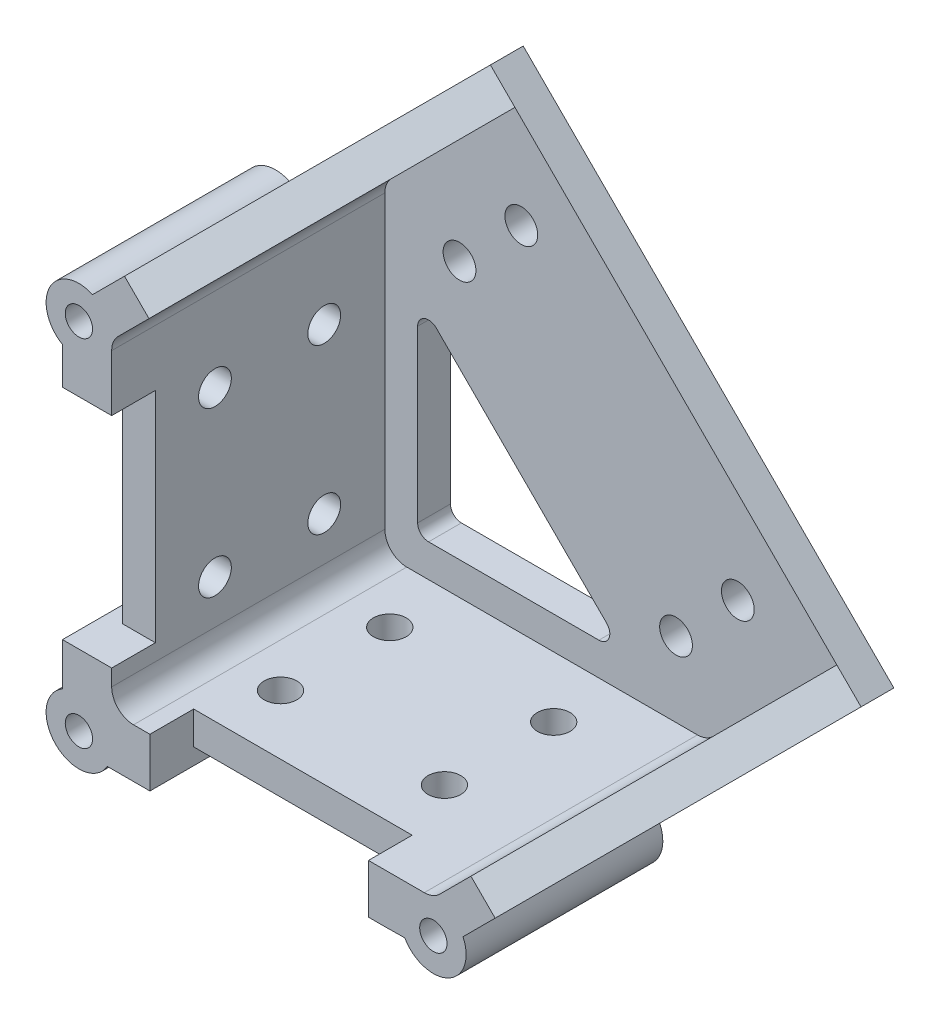
SolidWorks part; units mm, degrees
material "6061 合金"
ref_plane "前视基准面" through (0, 0, 0) normal (0, 0, 1) x (1, 0, 0)
ref_plane "上视基准面" through (0, 0, 0) normal (0, 1, 0) x (1, 0, 0)
ref_plane "右视基准面" through (0, 0, 0) normal (1, 0, 0) x (0, 0, -1)
sketch "草图1" plane through (0, 0, 0) normal (0, 0, 1) x (1, 0, 0)
  line L0 (-12.5966, 12.5) -> (15.5, 12.5) construction
  line L1 (-15.5, -15.5) -> (15.5, -15.5) construction
  line L2 (-15.5, -15.5) -> (-15.5, 15.5) construction
  line L3 (-15.5, 15.5) -> (15.5, 15.5) construction
  line L4 (15.5, -15.5) -> (15.5, 15.5) construction
  line L5 (-15.5, -15.5) -> (15.5, 15.5) construction
  line L6 (-15.5, 15.5) -> (15.5, -15.5) construction
  line L7 (12.5, 15.5) -> (12.5, -18.9326) construction
  line L8 (-7.5, -17) -> (-7.5, -15.5)
  line L9 (-7.5, 15.5) -> (-7.5, -18.9326) construction
  line L10 (-7.5, -15.5) -> (12.5, -15.5)
  line L11 (-15.5, 12.5) -> (-15.5, -7.5)
  line L12 (-12.9019, -17) -> (-7.5, -17)
  line L13 (-15.5, -7.5) -> (-17, -7.5)
  line L14 (15.5, 12.5) -> (15.5, 3)
  line L15 (15.5, -3) -> (15.5, -15.5)
  line L16 (3, 15.5) -> (12.5, 15.5)
  line L17 (-15.5, 15.5) -> (-3, 15.5)
  line L18 (-18.5, 12.5) -> (-15.5, 12.5)
  line L19 (-17, -7.5) -> (-17, -12.9019)
  line L20 (12.5, 12.5) -> (12.5, -12.5)
  line L21 (12.5, -15.5) -> (12.5, -18.5)
  line L22 (12.5, 15.5) -> (15.5, 15.5)
  line L23 (15.5, 15.5) -> (15.5, 12.5)
  line L24 (12.5, -12.5) -> (-12.5, -12.5)
  line L25 (-12.5, -12.5) -> (-12.5, 12.5)
  line L26 (-12.5, 12.5) -> (12.5, 12.5)
  circle A0 centre (0, 15.5) radius 1.5
  circle A1 centre (15.5, 0) radius 1.5
  circle A2 centre (-15.5, -15.5) radius 1.25
  arc A3 (3, 15.5) -> (-3, 15.5) centre (0, 15.5) ccw
  arc A4 (15.5, -3) -> (15.5, 3) centre (15.5, 0) ccw
  arc A5 (-17, -12.9019) -> (-12.9019, -17) centre (-15.5, -15.5) ccw
  arc A6 (-15.5, 15.5) -> (-18.5, 12.5) centre (-15.5, 12.5) ccw
  arc A7 (12.5, -18.5) -> (15.5, -15.5) centre (12.5, -15.5) ccw
  circle A9 centre (0, 15.5) radius 3 construction
  circle A10 centre (15.5, 0) radius 3 construction
  point P0 (0, 0)
  dimension "D6" = 3
  dimension "D7" = 3
  dimension "D8" = 2.5
  dimension "D10" = 6
  dimension "D12" = 1.5
  dimension "D1" = 31
  dimension "D2" = 3
  dimension "D3" = 3
  dimension "D11" = 1.5
  dimension "D4" = 20
  dimension "D15" = 25
  dimension "D5" = 20
  dimension "D9" = 1.5
extrude "凸台-拉伸1" add sketch "草图1" along normal blind 26
cosmetic thread "装饰螺纹线3" parameters "D2"=3
fillet "圆角1" radius 3 1 edges at (15.5, 15.5, 13)
fillet "圆角3" radius 1 2 edges at (-7.5, -17, 13) (-17, -7.5, 13)
sketch "草图3" plane through (0, 0, 26) normal (0, 0, 1) x (1, 0, 0)
  line L0 (-15.5, -7.5) -> (-15.5, -9)
  line L1 (-15.5, -9) -> (-17, -9)
  line L2 (-17, -8.5) -> (-17, -12.9019) construction
  line L3 (-17, -9) -> (-17, -7.5)
  line L4 (-17, -7.5) -> (-15.5, -7.5)
  line L5 (-7.5, -15.5) -> (-9, -15.5)
  line L6 (-9, -15.5) -> (-9, -17)
  line L7 (-12.9019, -17) -> (-8.5, -17) construction
  line L8 (-9, -17) -> (-7.5, -17)
  line L9 (-7.5, -17) -> (-7.5, -15.5)
  dimension "D1" = 1.5
  dimension "D2" = 1.5
extrude "切除-拉伸2" cut sketch "草图3" against normal through all
ref_plane "基准面1" through (0, 0, 0) normal (0.7071, -0.7071, 0) x (-0.7071, -0.7071, 0)
ref_plane "基准面2" through (0, 0, 0) normal (0.7071, -0.7071, 0) x (0, 0, -1)
sketch "草图4" plane through (0, 0, 26) normal (0, 0, 1) x (1, 0, 0)
  line L0 (12.5, -15.5) -> (12.5, -17)
  line L2 (12.5, -15.5) -> (12.5, -18.5) construction
  line L4 (12.5, -17) -> (11, -17)
  line L5 (11, -17) -> (11, -15.5)
  line L8 (11, -15.5) -> (12.5, -15.5)
  line L9 (-15.5, 12.5) -> (-17, 12.5)
  line L11 (-18.5, 12.5) -> (-15.5, 12.5) construction
  line L12 (-17, 12.5) -> (-17, 11)
  line L13 (-17, 11) -> (-15.5, 11)
  line L14 (-15.5, 12.5) -> (-15.5, -9) construction
  line L15 (-15.5, 11) -> (-15.5, 12.5)
  dimension "D1" = 1.5
  dimension "D2" = 1.5
  dimension "D3" = 1.5
extrude "凸台-拉伸2" add sketch "草图4" against normal up to surface (26 mm away) up to face at (-1.6362, -1.6362, 0)
sketch "草图5" plane through (0, 0, 26) normal (0, 0, 1) x (1, 0, 0)
  line L0 (15.5, -15.5) -> (15.5, -3) construction
  line L1 (-15.5, 15.5) -> (-18.127, 17.5054)
  line L2 (-18.127, 17.5054) -> (-21.2889, 12.8134)
  line L3 (-21.2889, 12.8134) -> (-20.0914, 10.7864)
  line L4 (-20.0914, 10.7864) -> (-17, 12.5)
  line L5 (15.5, -15.5) -> (16.572, -16.2224)
  line L6 (16.572, -16.2224) -> (15.5, -18.1555)
  line L7 (15.5, -18.1555) -> (15.3575, -18.4125)
  line L8 (13.8432, -19.4236) -> (15.3575, -18.4125)
  line L9 (13.8432, -19.4236) -> (11.9198, -18.918)
  line L10 (11.9198, -18.918) -> (12.5, -17)
  arc A0 (12.5, -17) -> (15.5, -15.5) centre (12.376, -13.0019) ccw
  arc A1 (12.5, -18.5) -> (15.5, -15.5) centre (12.5, -15.5) ccw construction
  arc A2 (-15.5, 15.5) -> (-17, 12.5) centre (-13.0019, 12.376) ccw
  dimension "D1" = 4
  dimension "D2" = 4
extrude "切除-拉伸3" cut sketch "草图5" against normal through all
fillet "圆角4" radius 3 2 edges at (-15.5, 15.5, 13) (15.5, -15.5, 13)
sketch "草图9" plane through (0, -17, 0) normal (0, -1, 0) x (1, 0, 0)
  circle A0 centre (8.5, 16.55) radius 1.5
  circle A1 centre (8.5, 6.55) radius 1.5
  circle A2 centre (-6.5, 6.55) radius 1.5
  circle A3 centre (-6.5, 16.55) radius 1.5
  dimension "D1" = 3
  dimension "D2" = 3
  dimension "D3" = 3
  dimension "D4" = 3
extrude "切除-拉伸6" cut sketch "草图9" against normal blind 10
mirror "镜向3" about plane through (0, 0, 0) normal (0.7071, -0.7071, 0) of "切除-拉伸6"
sketch "草图10" plane through (0, 12.5, 0) normal (0, -1, 0) x (1, 0, 0)
  circle A0 centre (-6.5, 16.55) radius 3
  circle A1 centre (8.5, 16.55) radius 3
  circle A2 centre (-6.5, 6.55) radius 3
  circle A3 centre (8.5, 6.55) radius 3
  dimension "D1" = 6
  dimension "D2" = 6
  dimension "D3" = 6
  dimension "D4" = 6
extrude "切除-拉伸7" cut sketch "草图10" against normal blind 10
mirror "镜向4" about plane through (0, 0, 0) normal (0.7071, -0.7071, 0) of "切除-拉伸7"
sketch "草图11" plane through (0, 0, 0) normal (0, 0, -1) x (-1, 0, 0)
  line L0 (13.9942, 15.5) -> (-15.5, -13.9942)
  line L1 (-15.5, -13.9942) -> (-22.6033, 9.551)
  line L2 (-22.6033, 9.551) -> (-15.8812, 22.0814)
  line L3 (-15.8812, 22.0814) -> (-1.7916, 22.8835)
  line L4 (-1.7916, 22.8835) -> (13.9942, 15.5)
extrude "切除-拉伸9" cut sketch "草图11" against normal through all
sketch "草图13" plane through (0, 0, 0) normal (0, 0, -1) x (-1, 0, 0)
  line L1 (-12.5, -10.9942) -> (-16.6778, -10.9942)
  line L2 (-12.5, -10.9942) -> (-12.5, -17.4756)
  line L3 (-12.5, -17.4756) -> (-16.6778, -17.4756)
  line L4 (-16.6778, -10.9942) -> (-16.6778, -17.4756)
  line L5 (10.9942, 12.5) -> (18.352, 12.5)
  line L6 (10.9942, 12.5) -> (10.9942, 16.3216)
  line L7 (10.9942, 16.3216) -> (18.352, 16.3216)
  line L8 (18.352, 12.5) -> (18.352, 16.3216)
extrude "切除-拉伸10" cut sketch "草图13" against normal through all
fillet "圆角6" radius 2 1 edges at (-12.5, -12.5, 13)
sketch "草图18" plane through (0, 0, 26) normal (0, 0, 1) x (1, 0, 0)
  line L0 (-12.5, 12.5) -> (12.5, -12.5)
  line L1 (12.5, -12.5) -> (-12.5, -12.5)
  line L2 (-12.5, -12.5) -> (-12.5, 12.5)
  line L3 (-9.5, -8.5) -> (-9.5, 2.8431)
  line L4 (-7.7929, 3.5503) -> (3.5503, -7.7929)
  line L5 (2.8431, -9.5) -> (-8.5, -9.5)
  line L6 (5.2574, -9.5) -> (-9.5, -9.5) construction
  line L7 (-9.5, 5.2574) -> (5.2574, -9.5) construction
  line L8 (-9.5, -9.5) -> (-9.5, 5.2574) construction
  arc A0 (2.8431, -9.5) -> (3.5503, -7.7929) centre (2.8431, -8.5) ccw
  arc A1 (-9.5, -8.5) -> (-8.5, -9.5) centre (-8.5, -8.5) ccw
  arc A2 (-9.5, 2.8431) -> (-7.7929, 3.5503) centre (-8.5, 2.8431) cw
  dimension "D2" = 1
  dimension "D1" = 3
extrude "凸台-拉伸5" add sketch "草图18" against normal blind 4 from offset 22 offset against normal yes
sketch "草图19" plane through (0, 0, 0) normal (0, 0, -1) x (-1, 0, 0)
  line L13 (17, 12.5) -> (12.5, 12.5)
  line L14 (12.5, 12.5) -> (-12.5, -12.5)
  line L15 (-12.5, -12.5) -> (-12.5, -17)
  line L16 (-12.5, -17) -> (-11, -17)
  line L17 (-11, -17) -> (-11, -15.5)
  line L18 (-11, -15.5) -> (9, -15.5)
  line L19 (9, -15.5) -> (9, -17)
  line L20 (9, -17) -> (12.9019, -17)
  line L21 (17, -12.9019) -> (17, -9)
  line L22 (17, -9) -> (15.5, -9)
  line L23 (15.5, -9) -> (15.5, 11)
  line L24 (15.5, 11) -> (17, 11)
  line L25 (17, 11) -> (17, 12.5)
  line L26 (17, 12.5) -> (12.5, 12.5)
  line L27 (12.5, 12.5) -> (-12.5, -12.5)
  line L28 (-12.5, -12.5) -> (-12.5, -17)
  line L29 (-12.5, -17) -> (-11, -17)
  line L30 (-11, -17) -> (-11, -15.5)
  line L31 (-11, -15.5) -> (9, -15.5)
  line L32 (9, -15.5) -> (9, -17)
  line L33 (9, -17) -> (12.9019, -17)
  line L34 (17, -12.9019) -> (17, -9)
  line L35 (17, -9) -> (15.5, -9)
  line L36 (15.5, -9) -> (15.5, 11)
  line L37 (15.5, 11) -> (17, 11)
  line L38 (17, 11) -> (17, 12.5)
  arc A1 (12.9019, -17) -> (17, -12.9019) centre (15.5, -15.5) ccw
  arc A2 (12.9019, -17) -> (17, -12.9019) centre (15.5, -15.5) ccw
  dimension "D1" = 0
extrude "凸台-拉伸6" add sketch "草图19" along normal blind 2
sketch "草图20" plane through (0, 0, 4) normal (0, 0, 1) x (1, 0, 0)
  line L3 (-10.5, -12.5) -> (12.5, -12.5)
  line L4 (12.5, -12.5) -> (-12.5, 12.5)
  line L5 (-12.5, 12.5) -> (-12.5, -10.5)
  line L6 (-10.5, -12.5) -> (12.5, -12.5)
  line L7 (12.5, -12.5) -> (-12.5, 12.5)
  line L8 (-12.5, 12.5) -> (-12.5, -10.5)
  line L9 (-8.5, -9.5) -> (2.8431, -9.5)
  line L10 (-8.5, -9.5) -> (2.8431, -9.5)
  line L11 (3.5503, -7.7929) -> (-7.7929, 3.5503)
  line L12 (3.5503, -7.7929) -> (-7.7929, 3.5503)
  line L13 (-9.5, 2.8431) -> (-9.5, -8.5)
  line L14 (-9.5, 2.8431) -> (-9.5, -8.5)
  arc A1 (-12.5, -10.5) -> (-10.5, -12.5) centre (-10.5, -10.5) ccw
  arc A2 (-12.5, -10.5) -> (-10.5, -12.5) centre (-10.5, -10.5) ccw
  arc A3 (2.8431, -9.5) -> (3.5503, -7.7929) centre (2.8431, -8.5) ccw
  arc A4 (2.8431, -9.5) -> (3.5503, -7.7929) centre (2.8431, -8.5) ccw
  arc A7 (-7.7929, 3.5503) -> (-9.5, 2.8431) centre (-8.5, 2.8431) ccw
  arc A8 (-7.7929, 3.5503) -> (-9.5, 2.8431) centre (-8.5, 2.8431) ccw
  arc A9 (-9.5, -8.5) -> (-8.5, -9.5) centre (-8.5, -8.5) ccw
  arc A10 (-9.5, -8.5) -> (-8.5, -9.5) centre (-8.5, -8.5) ccw
  dimension "D1" = 0
  dimension "D2" = 0
extrude "切除-拉伸12" cut sketch "草图20" against normal blind 3
sketch "草图21" plane through (0, 0, 0) normal (0, 0, 1) x (1, 0, 0)
  line L3 (-8.5, -9.5) -> (2.8431, -9.5)
  line L4 (-8.5, -9.5) -> (2.8431, -9.5)
  line L5 (3.5503, -7.7929) -> (-7.7929, 3.5503)
  line L6 (3.5503, -7.7929) -> (-7.7929, 3.5503)
  line L7 (-9.5, 2.8431) -> (-9.5, -8.5)
  line L8 (-9.5, 2.8431) -> (-9.5, -8.5)
  circle A0 centre (-15.5, -15.5) radius 1.5
  arc A2 (2.8431, -9.5) -> (3.5503, -7.7929) centre (2.8431, -8.5) ccw
  arc A3 (2.8431, -9.5) -> (3.5503, -7.7929) centre (2.8431, -8.5) ccw
  arc A6 (-7.7929, 3.5503) -> (-9.5, 2.8431) centre (-8.5, 2.8431) ccw
  arc A7 (-7.7929, 3.5503) -> (-9.5, 2.8431) centre (-8.5, 2.8431) ccw
  arc A8 (-9.5, -8.5) -> (-8.5, -9.5) centre (-8.5, -8.5) ccw
  arc A9 (-9.5, -8.5) -> (-8.5, -9.5) centre (-8.5, -8.5) ccw
  dimension "D1" = 0
extrude "切除-拉伸13" cut sketch "草图21" against normal through all
sketch "草图22" plane through (0, 0, -2) normal (0, 0, -1) x (-1, 0, 0)
  line L0 (12.5, 12.5) -> (-16.9362, -16.9362) construction
  line L1 (-16.9362, -16.9362) -> (16.9827, 16.9827) construction
  line L2 (17, 11) -> (16.9827, 16.9827) construction
  line L3 (-16.9362, -16.9362) -> (-17, -17) construction
  line L4 (-11, -17) -> (-17, -17) construction
  line L5 (12.5, 12.5) -> (17, 12.5)
  line L6 (17, 12.5) -> (16.9827, 16.9827)
  line L7 (-12.5, -12.5) -> (-12.5, -17)
  line L8 (-12.5, -17) -> (-16.9362, -16.9362)
  line L9 (-16.9362, -16.9362) -> (-31.0784, -2.7941)
  line L10 (16.9827, 16.9827) -> (2.8406, 31.1249)
  line L11 (2.8406, 31.1249) -> (-31.0784, -2.7941)
  line L12 (-12.5, -12.5) -> (12.5, 12.5)
  dimension "D1" = 20
  dimension "D2" = 20
  dimension "D3" = 90
extrude "凸台-拉伸7" add sketch "草图22" against normal up to surface (28 mm away) up to face at (-7.5929, -7.5929, 26)
sketch "草图23" plane through (0, 0, 26) normal (0, 0, 1) x (1, 0, 0)
  line L0 (-12.5, 12.5) -> (-12.5, 16.9827)
  line L1 (-12.5, 16.9827) -> (-0.5992, 28.8835)
  line L2 (-2.8406, 31.1249) -> (31.0784, -2.7941) construction
  line L5 (12.5, -12.5) -> (16.9362, -12.5)
  line L6 (16.9362, -12.5) -> (28.8603, -0.576)
  line L7 (28.8603, -0.576) -> (-0.5992, 28.8835)
  line L8 (-12.5, 12.5) -> (-12.5, 11.0875)
  line L9 (-12.5, 11.0875) -> (11.0875, -12.5)
  line L10 (-10.5, -12.5) -> (12.5, -12.5) construction
  line L11 (11.0875, -12.5) -> (12.5, -12.5)
extrude "切除-拉伸14" cut sketch "草图23" against normal up to surface (25 mm away) up to face at (-4.7954, -4.7954, 1)
sketch "草图24" plane through (0, 0, 26) normal (0, 0, 1) x (1, 0, 0)
  line L0 (-15.5, -15.5) -> (19.8589, -15.5) construction
  line L1 (-15.5, -15.5) -> (-15.5, 23.5934) construction
  line L2 (16.9362, -16.9362) -> (16.9362, -12.5) construction
  line L3 (-16.9827, 16.9827) -> (-12.5, 16.9827) construction
  circle A0 centre (16.9362, -15.5) radius 3
  circle A1 centre (-15.5, 16.9827) radius 3
  dimension "D1" = 6
  dimension "D2" = 6
extrude "凸台-拉伸8" add sketch "草图24" against normal up to surface (28 mm away) up to face at (-4.3676, -4.3559, -2)
sketch "草图25" plane through (0, 0, 26) normal (0, 0, 1) x (1, 0, 0)
  circle A0 centre (16.9362, -15.5) radius 1.25
  circle A1 centre (-15.5, 16.9827) radius 1.25
  dimension "D1" = 2.5
  dimension "D2" = 2.5
extrude "切除-拉伸16" cut sketch "草图25" against normal through all
cosmetic thread "装饰螺纹线1" parameters "D2"=3
cosmetic thread "装饰螺纹线2" parameters "D2"=3
sketch "草图26" plane through (14.7181, -14.7181, 0) normal (-0.7071, 0.7071, 0) x (0, 0, 1)
  line L0 (1, 20) -> (26, 20)
  line L1 (26, 20) -> (26, 8)
  line L2 (26, 3.1369) -> (26, 20) construction
  line L3 (26, 8) -> (1, 20)
  dimension "D1" = 12
extrude "切除-拉伸17" cut sketch "草图26" against normal mid plane 100
sketch "草图27" plane through (0, -15.5, 0) normal (0, -1, 0) x (1, 0, 0)
  line L0 (-9, 26) -> (-9, 22)
  line L1 (-9, -2) -> (-9, 26) construction
  line L2 (-9, 22) -> (11, 22)
  line L3 (11, -2) -> (11, 26) construction
  line L4 (11, 22) -> (11, 26)
  line L5 (11, 26) -> (-9, 26)
  dimension "D1" = 4
extrude "切除-拉伸18" cut sketch "草图27" against normal blind 5
ref_plane "基准面4" through (0, 0, 0) normal (0.7071, -0.7071, 0) x (0, 0, -1)
mirror "镜向5" about plane through (0, 0, 0) normal (0.7071, -0.7071, 0) of "切除-拉伸18"
sketch "草图28" plane through (0, 0, 1) normal (0, 0, 1) x (1, 0, 0)
  line L0 (-0.5992, 28.8835) -> (28.8603, -0.576) construction
  line L1 (-2.8406, 31.1249) -> (-11.3259, 22.6396) construction
  line L2 (-15.5, -15.5) -> (14.1305, 14.1538) construction
  circle A0 centre (-0.0122, 19.8112) radius 1.5
  circle A1 centre (-5.669, 14.1543) radius 1.5
  circle A2 centre (19.799, 0.0155) radius 1.5
  circle A3 centre (14.1466, -5.6458) radius 1.5
  dimension "D1" = 3
  dimension "D2" = 6
  dimension "D3" = 10
  dimension "D4" = 3
  dimension "D5" = 8
  dimension "D6" = 10
extrude "切除-拉伸19" cut sketch "草图28" against normal through all
fillet "圆角8" [suppressed] radius 2
sketch "草图29" plane through (0, 0, -2) normal (0, 0, -1) x (-1, 0, 0)
  circle A0 centre (15.5, 16.9827) radius 1.5
  circle A1 centre (-16.9362, -15.5) radius 1.5
  dimension "D1" = 3
extrude "凸台-拉伸9" add sketch "草图29" against normal blind 11
sketch "草图30" plane through (0, 0, -2) normal (0, 0, -1) x (-1, 0, 0)
  line L0 (14.2538, 19.7116) -> (16.9928, 16.9727)
  line L1 (16.9928, 14.3805) -> (16.9928, 16.9727)
  line L2 (-14.3232, -16.9738) -> (-16.8987, -16.9738)
  line L3 (-19.6504, -14.2221) -> (-16.8987, -16.9738)
  arc A0 (14.2538, 19.7116) -> (16.9928, 14.3805) centre (15.5, 16.9827) cw
  arc A1 (-19.6504, -14.2221) -> (-14.3232, -16.9738) centre (-16.9362, -15.5) ccw
extrude "切除-拉伸21" cut sketch "草图30" against normal blind 10
sketch "草图31" plane through (0, 0, -2) normal (0, 0, -1) x (-1, 0, 0)
  circle A0 centre (15.5, -15.5) radius 1.5
extrude "凸台-拉伸10" add sketch "草图31" against normal blind 11
sketch "草图32" plane through (0, 0, -2) normal (0, 0, -1) x (-1, 0, 0)
  line L0 (17, -12.9019) -> (17, -17)
  line L1 (12.9019, -17) -> (17, -17)
  arc A0 (17, -12.9019) -> (12.9019, -17) centre (15.5, -15.5) cw
extrude "切除-拉伸22" cut sketch "草图32" against normal blind 10
fillet "圆角9" radius 2 2 edges at (-12.5, 16.9827, 13.5) (16.9362, -12.5, 13.5)
sketch "草图35" plane through (0, 0, 1) normal (0, 0, 1) x (1, 0, 0)
  line L0 (-9.5, -8.5) -> (-9.5, 9.5)
  line L1 (-9.5, 9.5) -> (9.5, -9.5)
  line L2 (9.5, -9.5) -> (-8.5, -9.5)
  line L4 (-0.5992, 28.8835) -> (28.8603, -0.576) construction
  arc A0 (-8.5, -9.5) -> (-9.4982, -8.5606) centre (-8.5, -8.5) cw
  arc M14 (-9.5, 2.8431) -> (-7.7929, 3.5503) centre (-8.5, 2.8431) cw
  line M15 (-7.7929, 3.5503) -> (3.5503, -7.7929)
  arc M16 (3.5503, -7.7929) -> (2.8431, -9.5) centre (2.8431, -8.5) cw
  dimension "D1" = 20
extrude "切除-拉伸25" cut sketch "草图35" against normal blind 10 and the other way through all contours L2 L1 L0 M14 M15 M16
fillet "圆角10" radius 1 2 edges at (9.5, -9.5, -0.5) (-9.5, 9.5, -0.5)
